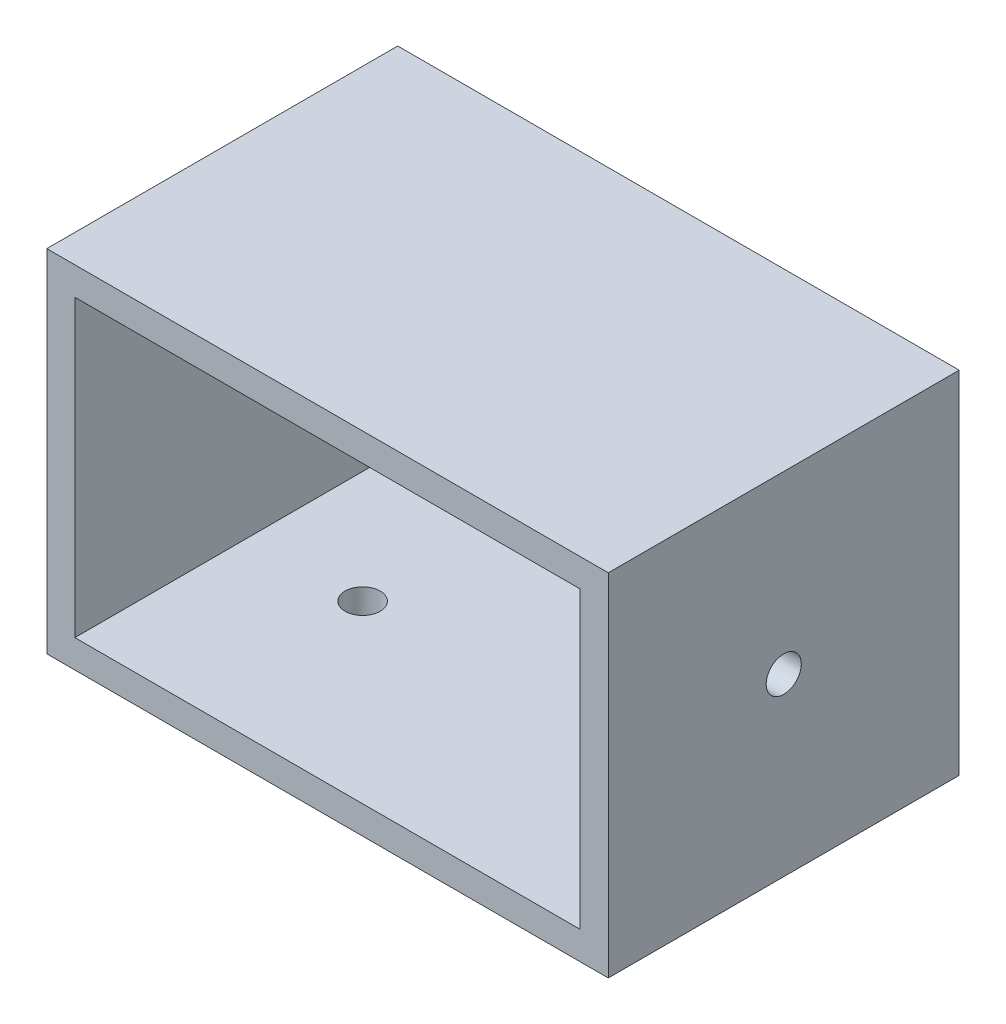
SolidWorks part; units mm, degrees
ref_plane "Front Plane" through (0, 0, 0) normal (0, 0, 1) x (1, 0, 0)
ref_plane "Top Plane" through (0, 0, 0) normal (0, 1, 0) x (1, 0, 0)
ref_plane "Right Plane" through (0, 0, 0) normal (1, 0, 0) x (0, 0, -1)
sketch "Sketch1" plane through (0, 0, 0) normal (0, 0, 1) x (1, 0, 0)
  line L0 (8, -8) -> (152, -8)
  line L1 (0, 0) -> (160, 0)
  line L2 (0, 0) -> (0, -100)
  line L3 (0, -100) -> (160, -100)
  line L4 (160, 0) -> (160, -100)
  line L5 (160, 0) -> (80, 0)
  line L9 (8, -8) -> (8, -92)
  line L10 (8, -92) -> (152, -92)
  line L11 (152, -8) -> (152, -92)
  dimension "160" = 160
  dimension "D2" = 100
  dimension "D5" = 8
extrude "Boss-Extrude1" add sketch "Sketch1" along normal blind 100
sketch "Sketch2" plane through (0, -100, 0) normal (0, -1, 0) x (1, 0, 0)
  line L0 (0, 0) -> (160, 0) construction
  line L1 (0, 100) -> (0, 0) construction
  circle A0 centre (40, 50) radius 5
  dimension "D1" = 50
  dimension "D2" = 40
extrude "Cut-Extrude1" cut sketch "Sketch2" against normal blind 10
sketch "Sketch3" plane through (160, 0, 0) normal (1, 0, 0) x (0, 0, -1)
  line L0 (-100, -100) -> (0, -100) construction
  line L1 (0, 0) -> (0, -100) construction
  circle A0 centre (-50, -50) radius 5
  dimension "D1" = 50
  dimension "D2" = 50
extrude "Cut-Extrude2" cut sketch "Sketch3" against normal blind 10
